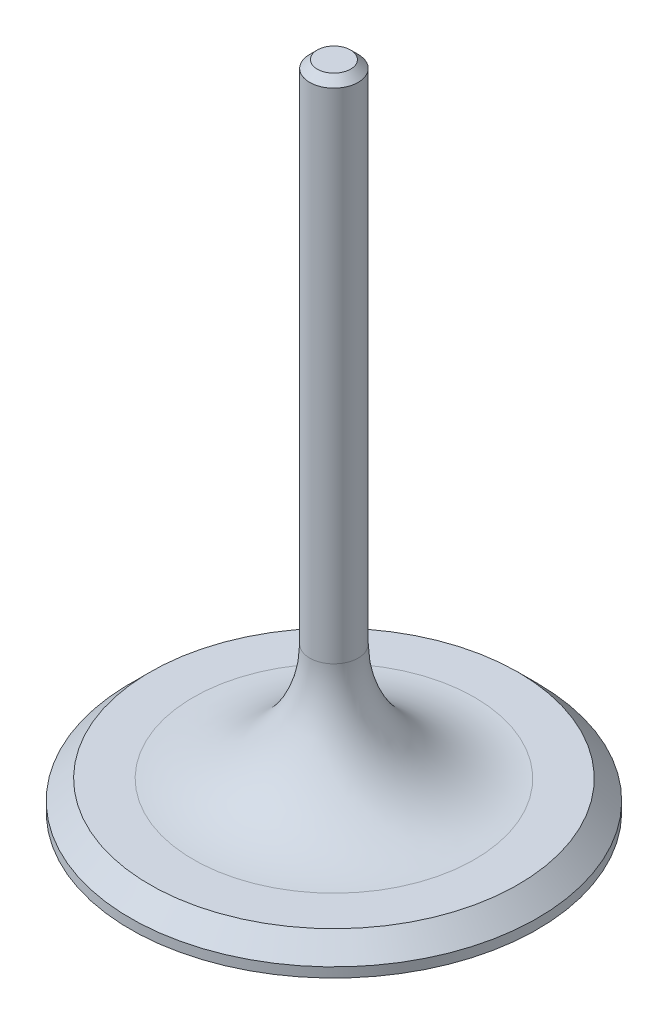
SolidWorks part; units mm, degrees
ref_plane "Front Plane" through (0, 0, 0) normal (0, 0, 1) x (1, 0, 0)
ref_plane "Top Plane" through (0, 0, 0) normal (0, 1, 0) x (1, 0, 0)
ref_plane "Right Plane" through (0, 0, 0) normal (1, 0, 0) x (0, 0, -1)
sketch "Sketch1" plane through (0, 0, 0) normal (0, 0, 1) x (1, 0, 0)
  line L0 (0, 0) -> (0, 52.8185) construction
  line L1 (0, 0) -> (-26.67, 0)
  line L2 (-26.67, 0) -> (-26.67, 1.27)
  line L3 (-26.67, 1.27) -> (-24.1315, 3.8085)
  line L4 (-24.1315, 3.8085) -> (-3.18, 3.8085)
  line L5 (-3.18, 3.8085) -> (-3.18, 85.4085)
  line L6 (-3.18, 85.4085) -> (0, 85.4085)
  line L7 (0, 85.4085) -> (0, 0)
  line L8 (-26.67, 1.27) -> (-20.8819, 1.27) construction
  dimension "D1" = 26.67
  dimension "D2" = 1.27
  dimension "D3" = 3.59
  dimension "D4" = 45
  dimension "D5" = 3.18
  dimension "D6" = 81.6
revolve "Revolve1" add sketch "Sketch1" angle 360 about L0
fillet "Fillet1" radius 15.25 1 edges at (0, 3.8085, -3.18)
chamfer "Chamfer1" distance 1 angle 45 1 edges at (0, 85.4085, -3.18)
